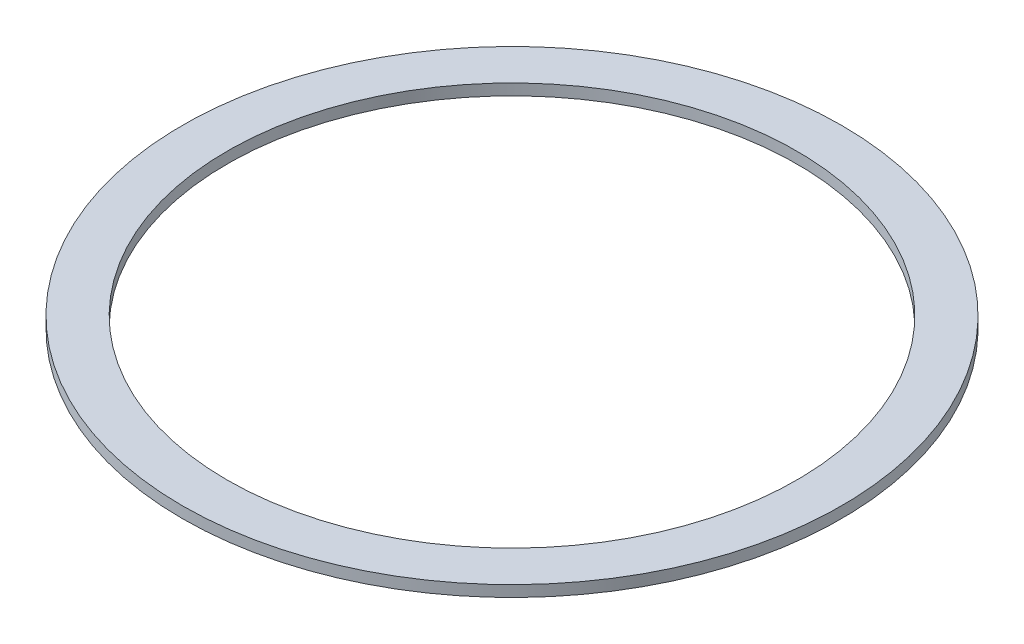
SolidWorks part; units mm, degrees
ref_plane "Front Plane" through (0, 0, 0) normal (0, 0, 1) x (1, 0, 0)
ref_plane "Top Plane" through (0, 0, 0) normal (0, 1, 0) x (1, 0, 0)
ref_plane "Right Plane" through (0, 0, 0) normal (1, 0, 0) x (0, 0, -1)
sketch "Sketch1" plane through (0, 0, 0) normal (0, 1, 0) x (1, 0, 0)
  circle A0 centre (0, 0) radius 255
  circle A1 centre (0, 0) radius 295
  dimension "D1" = 510
  dimension "D2" = 590
  dimension "D3" = 40
extrude "Boss-Extrude1" add sketch "Sketch1" along normal mid plane 10
